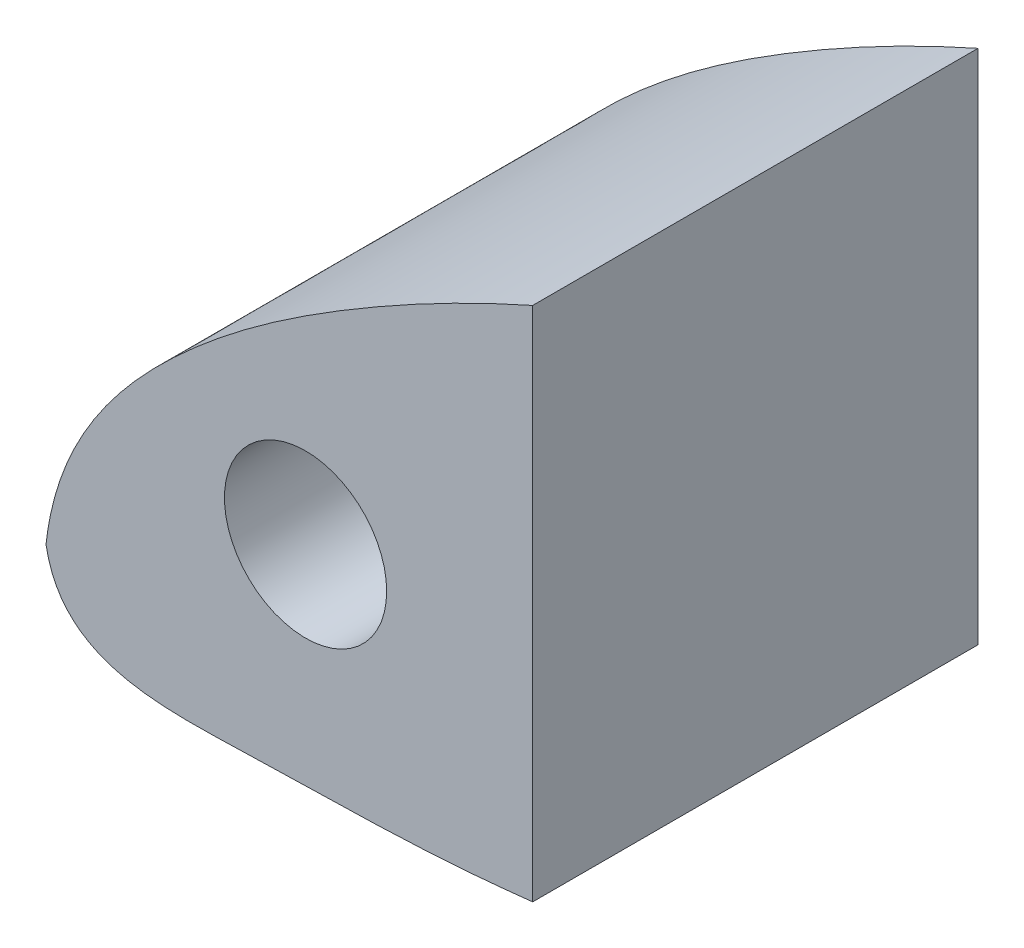
SolidWorks part; units mm, degrees
ref_plane "Front Plane" through (0, 0, 0) normal (0, 0, 1) x (1, 0, 0)
ref_plane "Top Plane" through (0, 0, 0) normal (0, 1, 0) x (1, 0, 0)
ref_plane "Right Plane" through (0, 0, 0) normal (1, 0, 0) x (0, 0, -1)
sketch "Sketch1" plane through (0, 0, 0) normal (0, 0, 1) x (1, 0, 0)
  spline S0 degree 3 poles (0.0006, 0.0001) (0.8106, 7.3592) (8.6491, 17.8566) (26.2867, 29.9752) (52.1111, 42.0692) (89.5976, 49.2908) (131.4008, 47.8848) (173.2567, 40.0411) (217.9611, 29.613) (256.9521, 19.5289) (290.3598, 8.711) (301.2732, 4.3828) (314.8169, -0.5162) (309.8463, 0.0001) knots 0 0 0 0 0.060864 0.113688 0.188609 0.312909 0.448482 0.557612 0.691544 0.852438 0.929756 0.976058 1 1 1 1
  spline S1 degree 3 poles (309.8463, 0.0001) (303.9568, 1.471) (293.9895, 2.094) (276.264, 4.5144) (260.8463, 5.4274) (235.8588, 7.8703) (205.1014, 8.8381) (157.7186, 9.0307) (110.4973, 6.1815) (66.5062, -0.5867) (36.4547, -6.0985) (15.3166, -6.1891) (1.2307, -6.9241) (0.0006, 0.0001) knots 0 0 0 0 0.057787 0.095275 0.171021 0.205339 0.335319 0.464904 0.658702 0.785512 0.893517 0.943092 1 1 1 1
extrude "Boss-Extrude1" add sketch "Sketch1" along normal blind 34.8615
sketch "Sketch2" plane through (0, 0, 34.8615) normal (0, 0, 1) x (1, 0, 0)
  circle A0 centre (20.32, 10.16) radius 6.35
  circle A1 centre (227.2963, 19.0501) radius 3.175
  dimension "D2" = 12.7
  dimension "D3" = 6.35
  dimension "D6" = 20.32
  dimension "D1" = 82.55
  dimension "D4" = 19.05
  dimension "D5" = 10.16
extrude "Cut-Extrude1" cut sketch "Sketch2" against normal through all
sketch "Sketch3" plane through (0, 0, 34.8615) normal (0, 0, 1) x (1, 0, 0)
  line L1 (38.1, 71.718) -> (331.2889, 71.718)
  line L2 (38.1, 71.718) -> (38.1, -66.2532)
  line L3 (38.1, -66.2532) -> (331.2889, -66.2532)
  line L4 (331.2889, 71.718) -> (331.2889, -66.2532)
  dimension "D1" = 38.1
extrude "Cut-Extrude2" cut sketch "Sketch3" against normal through all
